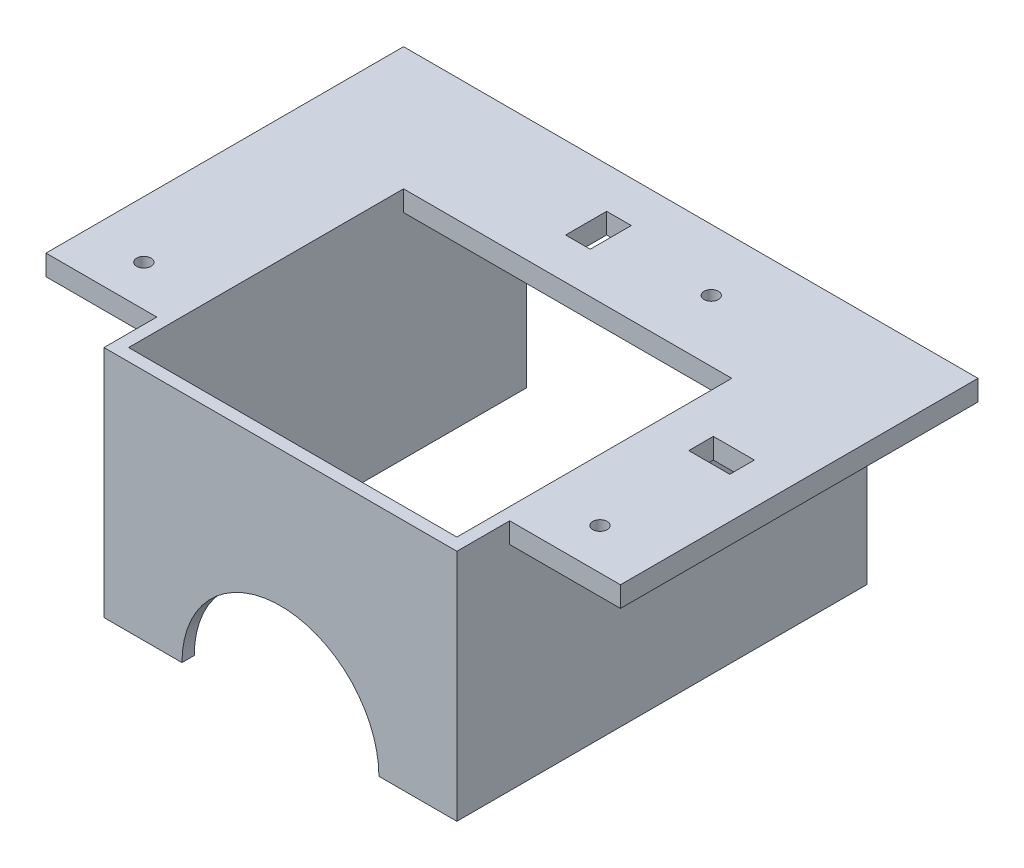
SolidWorks part; units mm, degrees
ref_plane "Front Plane" through (0, 0, 0) normal (0, 0, 1) x (1, 0, 0)
ref_plane "Top Plane" through (0, 0, 0) normal (0, 1, 0) x (1, 0, 0)
ref_plane "Right Plane" through (0, 0, 0) normal (1, 0, 0) x (0, 0, -1)
sketch "Sketch1" plane through (0, 0, 0) normal (0, 1, 0) x (1, 0, 0)
  line L0 (0, 0) -> (0, 100)
  line L1 (0, 100) -> (3, 100)
  line L2 (3, 100) -> (3, 3)
  line L3 (3, 3) -> (83, 3)
  line L4 (83, 3) -> (83, 100)
  line L5 (83, 100) -> (86, 100)
  line L6 (86, 100) -> (86, 0)
  line L7 (86, 0) -> (0, 0)
  dimension "D1" = 80
  dimension "D2" = 3
  dimension "D3" = 3
  dimension "D4" = 100
extrude "Boss-Extrude1" add sketch "Sketch1" along normal blind 52
sketch "Sketch2" plane through (0, 52, 0) normal (0, 1, 0) x (1, 0, 0)
  line L1 (83, 12.865) -> (113, 12.865)
  line L2 (83, 12.865) -> (83, 100)
  line L3 (83, 100) -> (113, 100)
  line L4 (113, 12.865) -> (113, 100)
  line L5 (3, 100) -> (-27, 100)
  line L6 (3, 100) -> (3, 12.865)
  line L7 (3, 12.865) -> (-27, 12.865)
  line L8 (-27, 100) -> (-27, 12.865)
  dimension "D1" = 30
  dimension "D2" = 87.135
extrude "Boss-Extrude2" add sketch "Sketch2" along normal blind 5
sketch "Sketch3" plane through (0, 57, 0) normal (0, 1, 0) x (1, 0, 0)
  line L0 (83, 100) -> (83, 12.865) construction
  line L1 (3, 100) -> (83, 100)
  line L2 (3, 100) -> (3, 70)
  line L3 (3, 70) -> (83, 70)
  line L4 (83, 100) -> (83, 70)
  dimension "D1" = 30
extrude "Boss-Extrude3" add sketch "Sketch3" against normal blind 5
sketch "Sketch5" plane through (0, 52, 0) normal (0, 1, 0) x (1, 0, 0)
  line L0 (0, 12.865) -> (0, 0)
  line L1 (0, 0) -> (86, 0)
  line L2 (86, 0) -> (86, 12.865)
  line L3 (86, 12.865) -> (83, 12.865)
  line L4 (83, 12.865) -> (83, 3)
  line L5 (83, 3) -> (3, 3)
  line L6 (83, 3) -> (3, 3) construction
  line L7 (3, 3) -> (3, 12.865)
  line L8 (3, 3) -> (3, 12.865) construction
  line L9 (0, 12.865) -> (3, 12.865) construction
  line L10 (0, 12.865) -> (3, 12.865)
extrude "Boss-Extrude4" add sketch "Sketch5" along normal blind 5
sketch "Sketch6" plane through (0, 0, 0) normal (0, 0, 1) x (1, 0, 0)
  line L0 (0, 0) -> (86, 0) construction
  line L1 (19, 0) -> (67, 0)
  arc A0 (19, 0) -> (67, 0) centre (43, 0) cw
  dimension "D1" = 24
  dimension "D2" = 19
extrude "Cut-Extrude2" cut sketch "Sketch6" against normal blind 5 contours A0 L1
sketch "Sketch7" plane through (0, 57, 0) normal (0, 1, 0) x (1, 0, 0)
  line L0 (113, 12.865) -> (113, 100) construction
  line L1 (3, 70) -> (83, 70) construction
  line L2 (-27, 12.865) -> (0, 12.865) construction
  line L3 (86, 12.865) -> (113, 12.865) construction
  line L4 (83, 70) -> (83, 3) construction
  circle A0 centre (-13.1498, 22.865) radius 1.75
  circle A1 centre (63, 85) radius 1.75
  circle A2 centre (98, 22.865) radius 1.75
  dimension "D1" = 3.5
  dimension "D2" = 3.5
  dimension "D3" = 3.5
  dimension "D4" = 50
  dimension "D5" = 15
  dimension "D6" = 10
  dimension "D7" = 10
  dimension "D8" = 15
extrude "Cut-Extrude3" cut sketch "Sketch7" against normal through all
sketch "Sketch8" plane through (0, 57, 0) normal (0, 1, 0) x (1, 0, 0)
  line L0 (38.5, 73.9695) -> (38.5, 95.4695) construction
  line L1 (103, 55.5) -> (93, 55.5)
  line L2 (103, 55.5) -> (103, 49.5)
  line L3 (103, 49.5) -> (93, 49.5)
  line L4 (93, 55.5) -> (93, 49.5)
  line L5 (32.5, 80) -> (38.5, 80)
  line L6 (32.5, 80) -> (32.5, 90)
  line L7 (32.5, 90) -> (38.5, 90)
  line L8 (38.5, 80) -> (38.5, 90)
  line L9 (87.25, 49.5) -> (108.75, 49.5) construction
  line L10 (98, 22.865) -> (98, 100) construction
  line L11 (113, 100) -> (-27, 100) construction
  line L12 (63, 85) -> (18.6962, 85) construction
  dimension "D1" = 10
  dimension "D2" = 6
  dimension "D3" = 10
  dimension "D4" = 6
  dimension "D5" = 5
  dimension "D6" = 5
extrude "Cut-Extrude4" cut sketch "Sketch8" against normal through all
